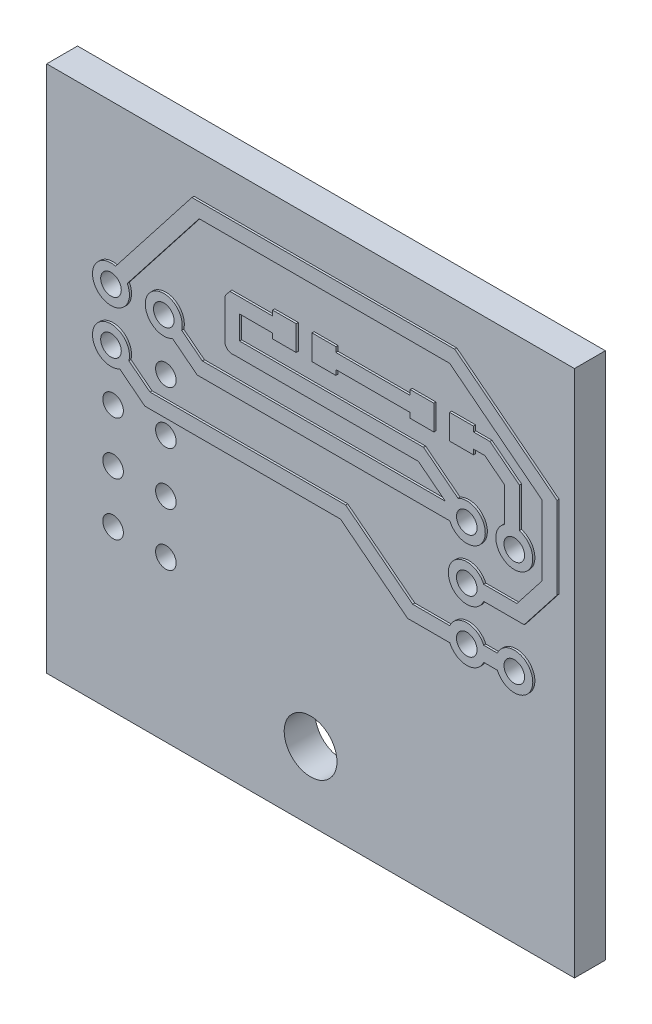
SolidWorks part; units mm, degrees
ref_plane "Front Plane" through (0, 0, 0) normal (0, 0, 1) x (1, 0, 0)
ref_plane "Top Plane" through (0, 0, 0) normal (0, 1, 0) x (1, 0, 0)
ref_plane "Right Plane" through (0, 0, 0) normal (1, 0, 0) x (0, 0, -1)
sketch "Sketch1" plane through (0, 0, 0) normal (0, 0, 1) x (1, 0, 0)
  line L1 (12.7, -12.7) -> (-12.7, -12.7)
  line L2 (12.7, -12.7) -> (12.7, 12.7)
  line L3 (12.7, 12.7) -> (-12.7, 12.7)
  line L4 (-12.7, -12.7) -> (-12.7, 12.7)
  line L5 (12.7, -12.7) -> (-12.7, 12.7) construction
  line L6 (12.7, 12.7) -> (-12.7, -12.7) construction
  point P0 (0, 0)
  dimension "D1" = 25.4
  dimension "D2" = 25.4
extrude "Boss-Extrude1" add sketch "Sketch1" along normal blind 1.5875
sketch "Sketch2" plane through (0, 0, 1.5875) normal (0, 0, 1) x (1, 0, 0)
  line L0 (-9.4331, -4.5064) -> (-9.7598, -5.4203) construction
  line L1 (-9.4909, 4.6681) -> (-9.8076, 5.5539) construction
  line L5 (-6.7791, -2.9166) -> (-7.1124, -1.9845) construction
  line L6 (-6.7281, 3.0592) -> (-7.0578, 2.1371) construction
  circle A0 centre (-9.5031, 5.1632) radius 0.4953
  circle A1 centre (-6.9631, 5.1632) radius 0.4953
  circle A2 centre (-6.9631, 2.6232) radius 0.4953
  circle A3 centre (-6.9631, 0.0832) radius 0.4953
  circle A4 centre (-6.9631, -2.4568) radius 0.4953
  circle A5 centre (-6.9631, -4.9968) radius 0.4953
  circle A6 centre (-9.5031, 2.6232) radius 0.4953
  circle A7 centre (-9.5031, 0.0832) radius 0.4953
  circle A8 centre (-9.5031, -2.4568) radius 0.4953
  circle A9 centre (-9.5031, -4.9968) radius 0.4953
  point P0 (-7.8219, 0)
  dimension "D1" = 2
  dimension "D3" = 0.9906
  dimension "D2" = 5
extrude "Cut-Extrude1" cut sketch "Sketch2" against normal blind 2.54 contours A0 | A1 | A6 | A2 | A7 | A3 | A8 | A4 | A9 | A5
sketch "Sketch4" plane through (0, 0, 1.5875) normal (0, 0, 1) x (1, 0, 0)
  line L0 (12.7, -12.7) -> (12.7, 12.7) construction
  line L1 (12.7, 12.7) -> (-12.7, 12.7) construction
  circle A0 centre (7.62, 3.81) radius 0.4953
  circle A1 centre (7.62, 1.27) radius 0.4953
  circle A2 centre (7.62, -1.27) radius 0.4953
  circle A3 centre (9.906, -1.27) radius 0.4953
  circle A4 centre (9.906, 3.81) radius 0.4953
  point P14 (0, 0)
  point P15 (0, 0)
  point P16 (0, 0)
  dimension "D1" = 0.9906
  dimension "D6" = 2.286
  dimension "D7" = 0.9906
  dimension "D2" = 2.54
  dimension "D3" = 2.54
  dimension "D4" = 5.08
  dimension "D5" = 8.89
extrude "Cut-Extrude2" cut sketch "Sketch4" against normal blind 2.54
sketch "Sketch5" plane through (0, 0, 1.5875) normal (0, 0, 1) x (1, 0, 0)
  line L0 (-9.5031, 5.1632) -> (-5.4341, 10.3713)
  line L1 (-5.4341, 10.3713) -> (6.9195, 10.3713)
  line L2 (11.6043, 6.7112) -> (11.6043, 3.0583)
  line L3 (10.2071, 1.27) -> (7.62, 1.27)
  line L4 (6.9195, 10.3713) -> (11.6043, 6.7112)
  line L5 (7.62, -1.27) -> (4.8944, -1.27)
  line L6 (4.8944, -1.27) -> (1.6647, 1.2533)
  line L7 (5.1986, 3.81) -> (-5.2311, 3.81)
  line L8 (-5.2311, 3.81) -> (-6.9631, 5.1632)
  line L9 (1.6647, 1.2533) -> (-7.7496, 1.2533)
  line L10 (5.1986, 3.81) -> (7.62, 3.81)
  line L11 (4.8944, 7.9738) -> (6.0344, 7.9738)
  line L12 (-1.7321, 7.9738) -> (-0.5921, 7.9738)
  line L13 (-1.7321, 7.9738) -> (-1.7321, 6.7738)
  line L14 (-1.7321, 6.7738) -> (-0.5921, 6.7738)
  line L15 (-0.5921, 7.9738) -> (-0.5921, 6.7738)
  line L16 (-1.7321, 7.9738) -> (-0.5921, 6.7738) construction
  line L17 (-1.7321, 6.7738) -> (-0.5921, 7.9738) construction
  line L18 (0.1679, 7.9738) -> (1.3179, 7.9738)
  line L19 (0.1679, 7.9738) -> (0.1679, 6.7738)
  line L20 (0.1679, 6.7738) -> (1.3179, 6.7738)
  line L21 (1.3179, 7.9738) -> (1.3179, 6.7738)
  line L22 (0.1679, 7.9738) -> (1.3179, 6.7738) construction
  line L23 (0.1679, 6.7738) -> (1.3179, 7.9738) construction
  line L24 (4.8944, 7.9738) -> (4.8944, 6.7738)
  line L25 (4.8944, 6.7738) -> (6.0344, 6.7738)
  line L26 (6.0344, 7.9738) -> (6.0344, 6.7738)
  line L27 (4.8944, 7.9738) -> (6.0344, 6.7738) construction
  line L28 (4.8944, 6.7738) -> (6.0344, 7.9738) construction
  line L29 (6.7944, 7.9738) -> (7.9444, 7.9738)
  line L30 (6.7944, 7.9738) -> (6.7944, 6.7738)
  line L31 (6.7944, 6.7738) -> (7.9444, 6.7738)
  line L32 (7.9444, 7.9738) -> (7.9444, 6.7738)
  line L33 (6.7944, 7.9738) -> (7.9444, 6.7738) construction
  line L34 (6.7944, 6.7738) -> (7.9444, 7.9738) construction
  line L35 (7.62, 3.81) -> (5.415, 5.5327)
  line L36 (5.415, 5.5327) -> (-3.6822, 5.5327)
  line L37 (-3.6695, 5.5228) -> (-3.6695, 7.2944)
  line L38 (7.3694, 7.3738) -> (8.6099, 7.3738)
  line L39 (9.7972, 6.4462) -> (9.7972, 3.9733)
  line L40 (-1.5479, 7.3738) -> (-3.6075, 7.3738)
  line L41 (1.1286, 7.3738) -> (5.1995, 7.3738)
  line L42 (7.62, -1.27) -> (9.906, -1.27)
  line L45 (-7.7496, 1.2533) -> (-9.5031, 2.6232)
  line L46 (10.2071, 1.27) -> (11.6043, 3.0583)
  line L48 (8.6099, 7.3738) -> (9.7972, 6.4462)
  line L49 (-3.6822, 5.5327) -> (-3.6695, 5.5228)
  line L50 (-3.6695, 5.5228) -> (-3.6695, 7.2944)
  line L51 (-3.6695, 7.2944) -> (-3.6075, 7.3738)
  line L52 (-9.2229, 4.9443) -> (-5.2607, 10.0157)
  line L53 (-5.2607, 10.0157) -> (6.797, 10.0157)
  line L54 (6.797, 10.0157) -> (11.2487, 6.5377)
  line L55 (11.2487, 6.5377) -> (11.2487, 3.1807)
  line L56 (10.0337, 1.6256) -> (11.2487, 3.1807)
  line L57 (10.0337, 1.6256) -> (7.62, 1.6256)
  line L58 (7.3694, 7.0182) -> (8.4875, 7.0182)
  line L59 (8.4875, 7.0182) -> (9.4416, 6.2728)
  line L60 (9.4416, 6.2728) -> (9.4416, 4.2822)
  line L61 (9.4416, 4.2822) -> (9.4416, 4.2822)
  line L63 (7.62, -1.6256) -> (9.906, -1.6256)
  line L64 (7.62, -0.9144) -> (9.906, -0.9144)
  line L65 (6.8052, -0.9144) -> (5.0168, -0.9144)
  line L66 (5.0168, -0.9144) -> (1.7872, 1.6089)
  line L67 (1.7872, 1.6089) -> (-7.6272, 1.6089)
  line L68 (-7.6272, 1.6089) -> (-9.2842, 2.9035)
  line L69 (-5.3535, 3.4544) -> (-7.1821, 4.883)
  line L70 (5.1986, 3.4544) -> (-5.3535, 3.4544)
  line L71 (5.1986, 3.4544) -> (8.4348, 3.4544)
  line L72 (8.481, 3.5886) -> (5.5375, 5.8883)
  line L73 (5.5375, 5.8883) -> (-3.3139, 5.8883)
  line L74 (-3.3139, 5.8883) -> (-3.3139, 7.2944)
  line L75 (1.1286, 7.0182) -> (5.1995, 7.0182)
  line L76 (-3.4455, 7.0182) -> (-3.4455, 7.0182)
  line L77 (-1.5479, 7.0182) -> (-3.4455, 7.0182)
  line L78 (-3.3139, 5.5228) -> (-3.3139, 5.5327)
  line L79 (-9.7834, 5.3822) -> (-5.6076, 10.7269)
  line L80 (-5.6076, 10.7269) -> (7.0419, 10.7269)
  line L81 (7.0419, 10.7269) -> (11.9599, 6.8846)
  line L82 (11.9599, 6.8846) -> (11.9599, 2.9359)
  line L83 (10.3805, 0.9144) -> (11.9599, 2.9359)
  line L84 (10.3805, 0.9144) -> (7.62, 0.9144)
  line L85 (7.3694, 7.7294) -> (8.7324, 7.7294)
  line L86 (8.7324, 7.7294) -> (10.1528, 6.6197)
  line L87 (10.1528, 6.6197) -> (10.1528, 3.6644)
  line L88 (5.5375, 5.8883) -> (-4.7149, 5.8883) construction
  line L89 (-3.3139, 5.5228) -> (-3.3139, 7.2944) construction
  line L90 (-10.16, 10.16) -> (-10.16, -10.16)
  line L91 (-10.16, -10.16) -> (10.16, -10.16)
  line L92 (8.4348, -1.6256) -> (4.7719, -1.6256)
  line L93 (4.7719, -1.6256) -> (1.5423, 0.8977)
  line L94 (1.5423, 0.8977) -> (-7.8721, 0.8977)
  line L95 (-7.8721, 0.8977) -> (-9.7221, 2.343)
  line L96 (-5.1086, 4.1656) -> (-6.7442, 5.4435)
  line L97 (5.1986, 4.1656) -> (-5.1086, 4.1656)
  line L98 (5.1986, 4.1656) -> (6.5873, 4.1656)
  line L99 (6.5873, 4.1656) -> (5.2926, 5.1771)
  line L100 (5.2926, 5.1771) -> (-3.5861, 5.1771)
  line L101 (-3.5861, 5.1771) -> (-3.5861, 5.1771)
  line L102 (1.1286, 7.7294) -> (5.1995, 7.7294)
  line L103 (-3.9497, 7.5133) -> (-3.7809, 7.7294)
  line L104 (-1.5479, 7.7294) -> (-3.7809, 7.7294)
  line L105 (-4.0251, 5.5228) -> (-4.0251, 7.2944)
  line L106 (9.6102, 3.5878) -> (6.1979, 2.3954) construction
  line L107 (9.4416, 4.2822) -> (5.4794, 2.8977) construction
  line L108 (5.4794, 2.8977) -> (5.5139, 0.4779) construction
  line L109 (5.8386, 2.6466) -> (5.8676, 0.6196) construction
  line L110 (6.1979, 2.3954) -> (6.2212, 0.7612) construction
  line L111 (6.2212, 0.7612) -> (8.4348, -1.6256) construction
  line L112 (5.8676, 0.6196) -> (7.62, -1.27) construction
  line L113 (5.5139, 0.4779) -> (6.8052, -0.9144) construction
  line L114 (9.5259, 3.935) -> (5.8386, 2.6466) construction
  line L115 (9.6102, 3.5878) -> (10.1528, 3.6644) construction
  line L116 (9.5259, 3.935) -> (9.7972, 3.9733) construction
  line L117 (10.16, -10.16) -> (10.16, 10.16)
  line L118 (10.16, 10.16) -> (-10.16, 10.16)
  line L119 (-10.16, 10.16) -> (-10.16, -10.16)
  line L120 (-10.16, -10.16) -> (10.16, -10.16)
  line L121 (10.16, -10.16) -> (10.16, 10.16)
  line L122 (10.16, 10.16) -> (-10.16, 10.16)
  line L123 (-4.7149, 5.8883) -> (-3.8884, 5.2426) construction
  line L124 (5.1986, 3.4544) -> (8.6527, 3.4544) construction
  line L125 (8.6527, 3.4544) -> (5.5375, 5.8883) construction
  arc A0 (-9.2229, 4.9443) -> (-9.7834, 5.3822) centre (-9.5031, 5.1632) cw
  arc A1 (7.62, 1.6256) -> (7.62, 0.9144) centre (7.62, 1.27) ccw
  arc A2 (7.3694, 7.0182) -> (7.3694, 7.7294) centre (7.3694, 7.3738) cw
  arc A3 (-9.2842, 2.9035) -> (-9.7221, 2.343) centre (-9.5031, 2.6232) ccw
  arc A4 (-7.1821, 4.883) -> (-6.7442, 5.4435) centre (-6.9631, 5.1632) cw
  arc A5 (-3.8884, 5.2426) -> (-3.5861, 5.1771) centre (-3.6695, 5.5228) ccw
  arc A6 (1.1286, 7.0182) -> (1.1286, 7.7294) centre (1.1286, 7.3738) cw
  arc A7 (5.1995, 7.0182) -> (5.1995, 7.7294) centre (5.1995, 7.3738) ccw
  arc A8 (-3.4455, 7.0182) -> (-3.9497, 7.5133) centre (-3.6695, 7.2944) cw
  arc A9 (-1.5479, 7.0182) -> (-1.5479, 7.7294) centre (-1.5479, 7.3738) ccw
  arc A10 (-3.5861, 5.1771) -> (-4.0251, 5.5228) centre (-3.6695, 5.5228) cw
  arc A11 (-3.3139, 7.2944) -> (-4.0251, 7.2944) centre (-3.6695, 7.2944) ccw
  circle A12 centre (-9.5031, 5.1632) radius 0.889
  circle A13 centre (-9.5031, 2.6232) radius 0.889
  circle A14 centre (-6.9631, 5.1632) radius 0.889
  circle A15 centre (7.62, 3.81) radius 0.889
  circle A16 centre (7.62, 1.27) radius 0.889
  circle A17 centre (7.62, -1.27) radius 0.889
  circle A18 centre (9.906, 3.8645) radius 0.889
  circle A20 centre (9.906, 3.8645) radius 0.4953
  circle A21 centre (7.62, 3.81) radius 0.4953 construction
  circle A22 centre (9.906, -1.27) radius 0.4953
  circle A23 centre (9.906, -1.27) radius 0.889
  circle A24 centre (7.62, -1.27) radius 0.4953 construction
  arc A25 (7.62, -1.6256) -> (7.62, -0.9144) centre (7.62, -1.27) cw
  arc A26 (9.906, -1.6256) -> (9.906, -0.9144) centre (9.906, -1.27) ccw
  point P16 (-1.1621, 7.3738)
  point P25 (0.7429, 7.3738)
  point P30 (5.4644, 7.3738)
  point P35 (7.3694, 7.3738)
  point P147 (-1.1621, 7.3738)
  point P148 (-1.5479, 7.3738)
  point P149 (-3.5782, 7.2944)
  point P150 (-3.6822, 5.5327)
  circle M33 centre (-6.9631, 0.0832) radius 0.4953
  circle M34 centre (-9.5031, -2.4568) radius 0.4953
  circle M35 centre (-6.9631, -2.4568) radius 0.4953
  circle M36 centre (-9.5031, -4.9968) radius 0.4953
  circle M37 centre (-6.9631, -4.9968) radius 0.4953
  circle M40 centre (-6.9631, 2.6232) radius 0.4953
  circle M41 centre (-9.5031, 0.0832) radius 0.4953
  line M43 (-12.7, 12.7) -> (-12.7, -12.7)
  line M44 (-12.7, -12.7) -> (12.7, -12.7)
  line M45 (12.7, -12.7) -> (12.7, 12.7)
  line M46 (12.7, 12.7) -> (-12.7, 12.7)
  dimension "D14" = 1.778
  dimension "D15" = 1.778
  dimension "D16" = 2.54
  dimension "D1" = 1.14
  dimension "D2" = 3.05
  dimension "D3" = 0.76
  dimension "D4" = 1.2
  dimension "D5" = 1.14
  dimension "D6" = 3.05
  dimension "D7" = 0.76
  dimension "D8" = 1.2
  dimension "D9" = 142
  dimension "D10" = 142
  dimension "D11" = 142
  dimension "D12" = 0.3556
  dimension "D19" = 2.286
  dimension "D20" = 2.286
  dimension "D13" = 0.3556
  dimension "D17" = 0.3556
  dimension "D18" = 0.3556
extrude "Cut-Extrude4" cut sketch "Sketch5" against normal blind 0.1016 contours A12 L79 L122 L119 | A23 L121 L120 L119 A13 A12 L122 L79 L80 L81 L82 L83 L84 M46 M43 M44 M45 | A23 L63 A17 L92 L93 L94 L95 A13 L119 L120 L121 M34 M36 M41 M37 M35 M33 | A23 L121 L84 A16 L57 L56 A18 L60 L59 L58 L32 L31 L30 L29 L85 L86 L87 L54 L53 L52 A12 L119 A13 L68 L67 L66 L65 A17 L64 L21 L102 L24 L11 L26 L25 L75 L20 L19 L18 A15 L71 M40 | A18 L121 L56 L55 L54 | L121 L122 L81
sketch "Sketch6" plane through (0, 0, 0) normal (0, 0, -1) x (-1, 0, 0)
  line L0 (12.7, -12.7) -> (-12.7, -12.7) construction
  circle A0 centre (0, -9.398) radius 1.27
  dimension "D1" = 2.54
  dimension "D2" = 3.302
extrude "Cut-Extrude5" cut sketch "Sketch6" against normal blind 2.54
